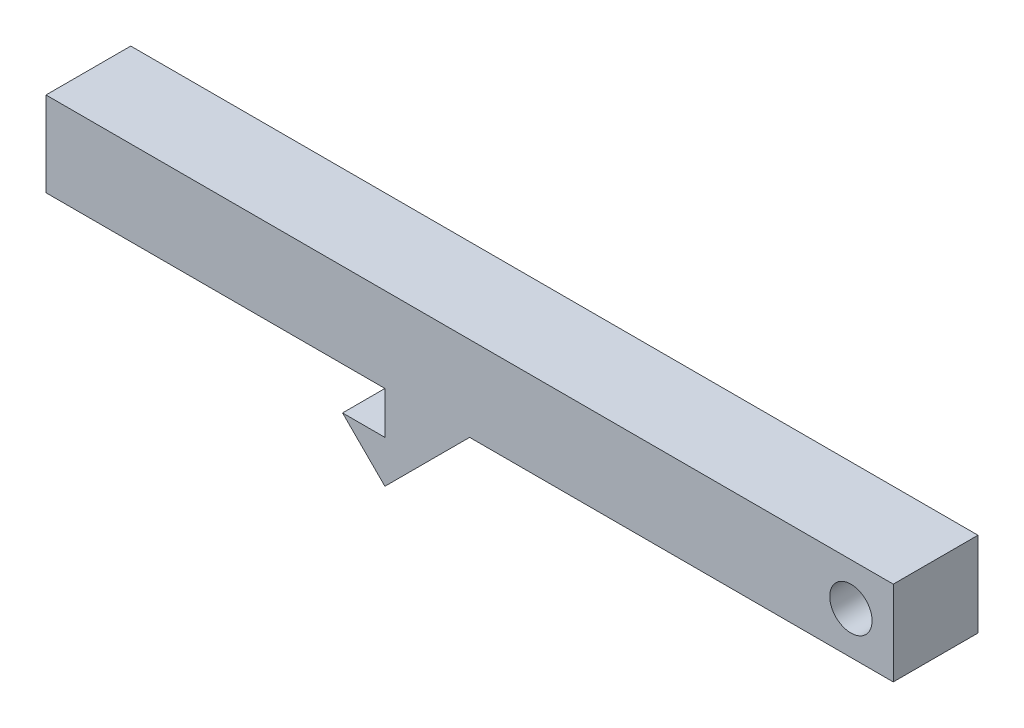
SolidWorks part; units mm, degrees
ref_plane "Front Plane" through (0, 0, 0) normal (0, 0, 1) x (1, 0, 0)
ref_plane "Top Plane" through (0, 0, 0) normal (0, 1, 0) x (1, 0, 0)
ref_plane "Right Plane" through (0, 0, 0) normal (1, 0, 0) x (0, 0, -1)
sketch "Sketch1" plane through (0, 0, 0) normal (0, 0, 1) x (1, 0, 0)
  line L0 (12.7, 0) -> (10.16, -2.54)
  line L5 (0, 0) -> (12.7, 0)
  line L6 (0, 0) -> (0, 2.54)
  line L7 (0, 2.54) -> (12.7, 2.54)
  line L8 (12.7, 0) -> (12.7, 2.54)
  line L9 (10.16, -2.54) -> (8.8902, -1.2702)
  line L10 (12.7, -2.54) -> (12.7, 0)
  line L11 (8.8902, -1.2702) -> (10.16, 0)
  line L12 (12.7, 2.54) -> (10.16, 2.54)
  line L20 (12.7, 2.54) -> (25.4, 2.54)
  line L21 (12.7, 2.54) -> (12.7, 0)
  line L22 (12.7, 0) -> (25.4, 0)
  line L23 (25.4, 2.54) -> (25.4, 0)
  line L24 (7.62, 0) -> (10.16, 0)
  line L26 (8.8902, -1.2702) -> (10.16, -1.2702)
  line L27 (10.16, 0) -> (10.16, -1.2702)
  circle A1 centre (24.13, 1.27) radius 0.635
  dimension "D8" = 1.27
  dimension "D9" = 1.27
  dimension "D10" = 1.27
  dimension "D1" = 2.54
  dimension "D2" = 12.7
  dimension "D3" = 2.54
  dimension "D4" = 45
  dimension "D5" = 5.08
  dimension "D6" = 12.7
  dimension "D7" = 2.54
extrude "Boss-Extrude1" add sketch "Sketch1" along normal blind 2.54
